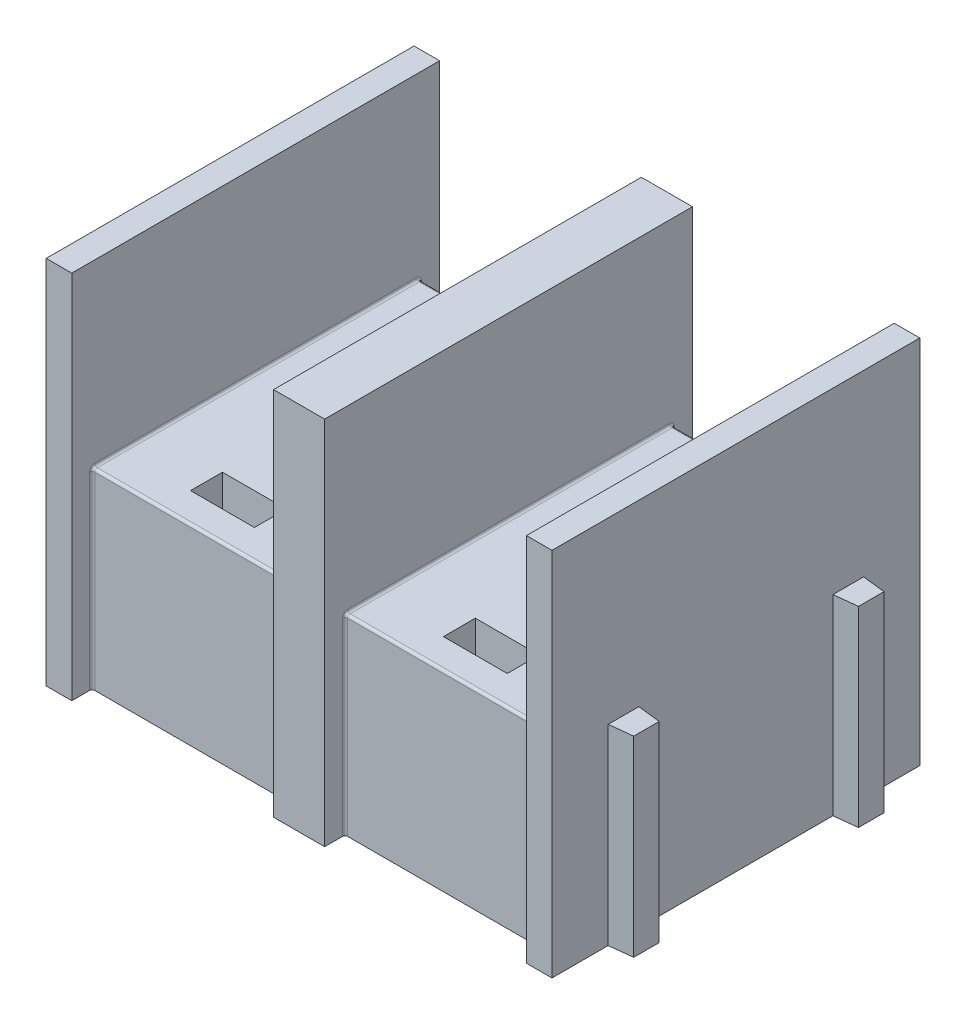
SolidWorks part; units mm, degrees
material "7075-T6, Plate (SS)"
ref_plane "Front" through (0, 0, 0) normal (0, 0, 1) x (1, 0, 0)
ref_plane "Top" through (0, 0, 0) normal (0, 1, 0) x (1, 0, 0)
ref_plane "Right" through (0, 0, 0) normal (1, 0, 0) x (0, 0, -1)
sketch "Sketch1" plane through (0, 0, 0) normal (0, 1, 0) x (1, 0, 0)
  line L0 (0, 7.2) -> (0, 0) construction
  line L1 (-9.9, 7.2) -> (9.9, 7.2)
  line L2 (-9.9, 7.2) -> (-9.9, -7.2)
  line L3 (-9.9, -7.2) -> (9.9, -7.2)
  line L4 (9.9, 7.2) -> (9.9, -7.2)
  line L5 (0, 0) -> (9.9, 0) construction
  dimension "D1" = 19.8
  dimension "D2" = 14.4
extrude "Boss-Extrude1" add sketch "Sketch1" along normal blind 14.5
sketch "Sketch3" plane through (0, 0, 7.2) normal (0, 0, 1) x (1, 0, 0)
  line L0 (0, 0) -> (0, 14.5) construction
  line L1 (-9.9, 0) -> (9.9, 0) construction
  line L2 (-9.9, 14.5) -> (9.9, 14.5) construction
  line L3 (9.9, 14.5) -> (9.9, 0) construction
  line L4 (1, 14.5) -> (8.9, 14.5)
  line L5 (1, 14.5) -> (1, 0)
  line L6 (1, 0) -> (8.9, 0)
  line L7 (8.9, 14.5) -> (8.9, 0)
  dimension "D1" = 1
  dimension "D2" = 1
extrude "Cut-Extrude1" cut sketch "Sketch3" against normal blind 0.8
mirror "Mirror1" about plane through (0, 0, 0) normal (0, 0, 1) of "Cut-Extrude1"
sketch "Sketch4" plane through (0, 0, 6.4) normal (0, 0, 1) x (1, 0, 0)
  line L0 (8.9, 0) -> (8.9, 14.5) construction
  line L1 (1, 14.5) -> (8.9, 14.5)
  line L2 (1, 14.5) -> (1, 7.5)
  line L3 (1, 7.5) -> (8.9, 7.5)
  line L4 (8.9, 14.5) -> (8.9, 7.5)
  line L5 (1, 0) -> (8.9, 0) construction
  dimension "D1" = 7.5
extrude "Cut-Extrude2" cut sketch "Sketch4" against normal through all
mirror "Mirror2" about plane through (0, 0, 0) normal (1, 0, 0) of "Mirror1", "Cut-Extrude2", "Cut-Extrude1"
sketch "Sketch5" plane through (0, 7.5, 0) normal (0, 1, 0) x (1, 0, 0)
  line L0 (0, 0) -> (11.4656, 0) construction
  line L1 (9.9, 5) -> (9.9, 3.8)
  line L2 (9.9, 3.8) -> (10.8, 3.9)
  line L3 (10.8, 3.9) -> (10.8, 4.9)
  line L4 (10.8, 4.9) -> (9.9, 5)
  line L5 (9.9, 4.4) -> (10.8, 4.4) construction
  line L6 (9.9, -7.2) -> (9.9, 7.2) construction
  line L7 (9.9, -5) -> (9.9, -3.8)
  line L8 (10.8, -4.9) -> (9.9, -5)
  line L9 (10.8, -3.9) -> (10.8, -4.9)
  line L10 (9.9, -3.8) -> (10.8, -3.9)
  dimension "D1" = 1.2
  dimension "D2" = 0.9
  dimension "D3" = 1
  dimension "D4" = 10
extrude "Boss-Extrude2" add sketch "Sketch5" against normal up to surface (7.5 mm away) up to face at (0, 0, 0)
sketch "Sketch6" plane through (0, 7.5, 0) normal (0, 1, 0) x (1, 0, 0)
  line L0 (0, 0) -> (-10.2729, 0) construction
  line L1 (-9.9, 5.05) -> (-9.9, 3.75)
  line L2 (-9.9, 7.2) -> (-9.9, -7.2) construction
  line L3 (-9.9, 3.75) -> (-8.9, 3.85)
  line L4 (-8.9, 3.85) -> (-8.9, 4.95)
  line L5 (-8.9, 4.95) -> (-9.9, 5.05)
  line L6 (-9.9, 4.4) -> (-8.9, 4.4) construction
  line L7 (-9.9, -5.05) -> (-9.9, -3.75)
  line L8 (-8.9, -4.95) -> (-9.9, -5.05)
  line L9 (-8.9, -3.85) -> (-8.9, -4.95)
  line L10 (-9.9, -3.75) -> (-8.9, -3.85)
  dimension "D1" = 1.3
  dimension "D2" = 1
  dimension "D3" = 1.1
  dimension "D4" = 10.1
fillet "Fillet1" radius 0.1 16 edges at (1, 3.75, 6.4) (8.9, 3.75, 6.4) (-8.9, 3.75, 6.4) (-1, 3.75, 6.4) (-4.95, 7.5, 6.4) (-8.9, 3.75, -6.4) (-4.95, 7.5, -6.4) (-1, 3.75, -6.4) (8.9, 3.75, -6.4) (1, 3.75, -6.4) (4.95, 7.5, 6.4) (4.95, 7.5, -6.4) (8.9, 7.5, 0) (1, 7.5, 0) (-8.9, 7.5, 0) (-1, 7.5, 0)
extrude "Cut-Extrude3" cut sketch "Sketch6" against normal up to surface (7.5 mm away) up to face at (2.3, 0, 0.1639)
sketch "Sketch7" plane through (0, 0, 0) normal (0, -1, 0) x (1, 0, 0)
  line L0 (0, 0) -> (0, -6.4222) construction
  line L1 (5, -4.4) -> (10.8, -4.4) construction
  line L2 (10.8, -4.9) -> (10.8, -3.9) construction
  circle A0 centre (-5, -4.4) radius 1
  circle A1 centre (5, -4.4) radius 1
  dimension "D2" = 2
  dimension "D1" = 10
extrude "Cut-Extrude4" cut sketch "Sketch7" against normal blind 5
sketch "Sketch8" plane through (0, 7.5, 0) normal (0, 1, 0) x (1, 0, 0)
  line L0 (0, 0) -> (4.95, 0) construction
  line L1 (3.7, 5.25) -> (6.2, 5.25)
  line L2 (3.7, 5.25) -> (3.7, 4)
  line L3 (3.7, 4) -> (6.2, 4)
  line L4 (6.2, 5.25) -> (6.2, 4)
  line L5 (3.7, -5.25) -> (3.7, -4)
  line L6 (3.7, -5.25) -> (6.2, -5.25)
  line L7 (6.2, -5.25) -> (6.2, -4)
  line L8 (3.7, -4) -> (6.2, -4)
  line L9 (4.95, 6.3) -> (4.95, 0) construction
  line L10 (8.8, 6.3) -> (1.1, 6.3) construction
  dimension "D1" = 2.5
  dimension "D2" = 10.5
  dimension "D3" = 1.25
extrude "Cut-Extrude5" cut sketch "Sketch8" against normal blind 2.5
mirror "Mirror3" about plane through (0, 0, 0) normal (1, 0, 0) of "Cut-Extrude5"
